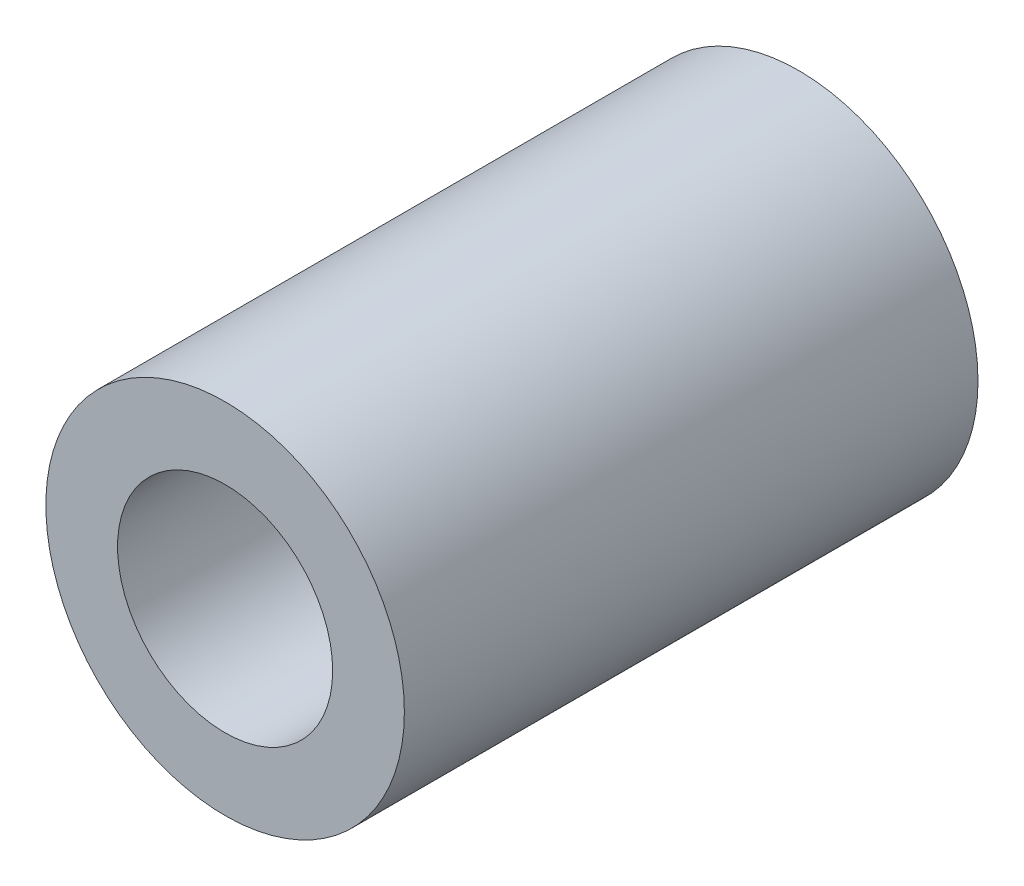
SolidWorks part; units mm, degrees
material "Polyetheretherketone (PEEK)"
ref_plane "Front Plane" through (0, 0, 0) normal (0, 0, 1) x (1, 0, 0)
ref_plane "Top Plane" through (0, 0, 0) normal (0, 1, 0) x (1, 0, 0)
ref_plane "Right Plane" through (0, 0, 0) normal (1, 0, 0) x (0, 0, -1)
sketch "Sketch1" plane through (0, 0, 0) normal (0, 0, 1) x (1, 0, 0)
  circle A0 centre (0, 0) radius 3.9688
  circle A1 centre (0, 0) radius 2.3813
  dimension "D1" = 4.7625
  dimension "D2" = 7.9375
extrude "Boss-Extrude1" add sketch "Sketch1" along normal blind 12.7
